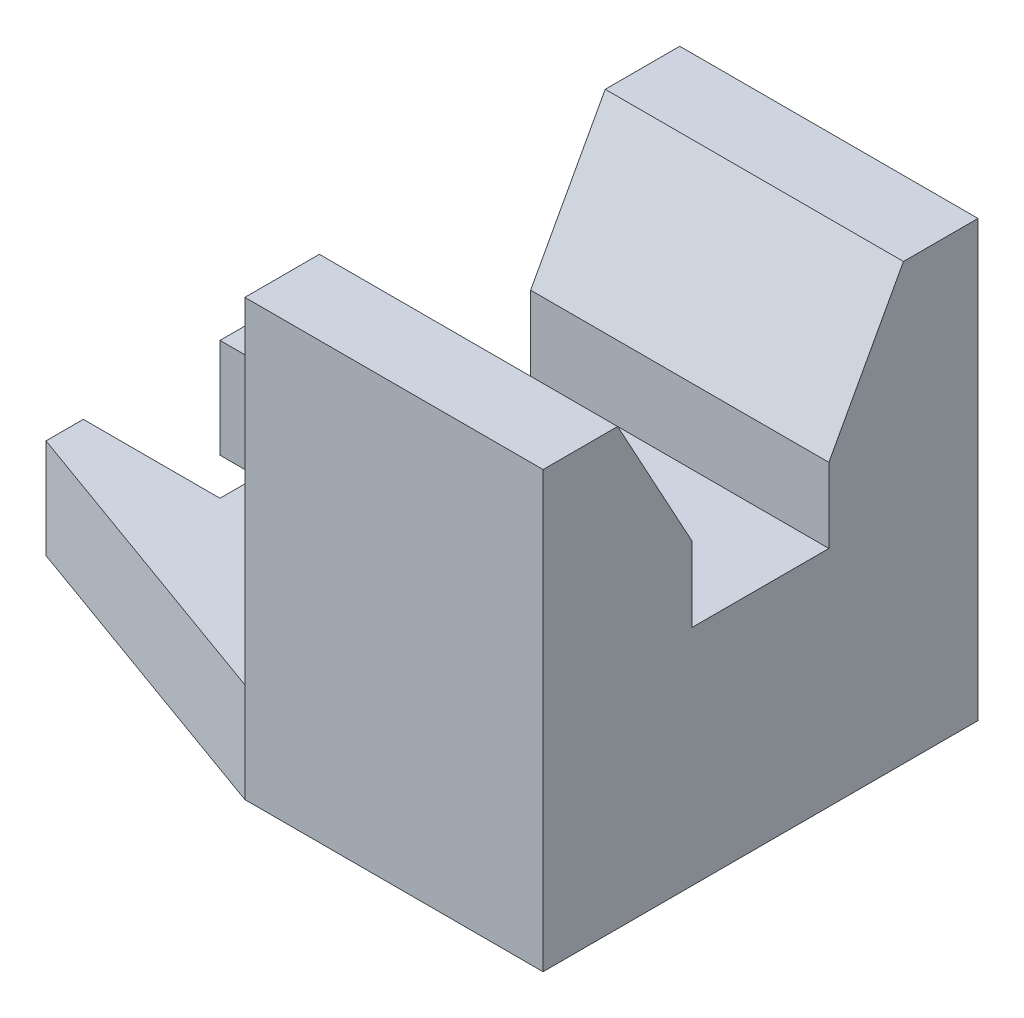
SolidWorks part; units mm, degrees
ref_plane "前视基准面" through (0, 0, 0) normal (0, 0, 1) x (1, 0, 0)
ref_plane "上视基准面" through (0, 0, 0) normal (0, 1, 0) x (1, 0, 0)
ref_plane "右视基准面" through (0, 0, 0) normal (1, 0, 0) x (0, 0, -1)
other "Configuration Table"
sketch "草图4" plane through (0, 0, 0) normal (0, 1, 0) x (1, 0, 0)
  line L0 (-12, 17.5) -> (-37, 8.5)
  line L1 (-12, -17.5) -> (12, -17.5)
  line L3 (-12, 17.5) -> (12, 17.5)
  line L4 (12, -17.5) -> (12, 17.5)
  line L5 (-12, -17.5) -> (12, 17.5) construction
  line L6 (-12, 17.5) -> (12, -17.5) construction
  line L7 (-37, 8.5) -> (-37, 5.5)
  line L8 (-37, 5.5) -> (-26, 5.5)
  line L9 (-26, 5.5) -> (-26, -5.5)
  line L10 (-1119.762, 0) -> (54868.3369, 0) construction
  line L11 (-12, -17.5) -> (-37, -8.5)
  line L12 (-37, -5.5) -> (-26, -5.5)
  line L13 (-37, -8.5) -> (-37, -5.5)
  point P0 (0, 0)
  point P14 (-26, 0)
  dimension "D1" = 17
  dimension "D2" = 11
  dimension "D3" = 11
  dimension "D4" = 24
  dimension "D5" = 49
  dimension "D6" = 35
extrude "凸台-拉伸2" add sketch "草图4" along normal blind 8
sketch "草图5" plane through (0, 8, 0) normal (0, 1, 0) x (1, 0, 0)
  line L1 (12, 17.5) -> (-12, 17.5)
  line L2 (12, 17.5) -> (12, -17.5)
  line L3 (12, -17.5) -> (-12, -17.5)
  line L4 (-12, 17.5) -> (-12, -17.5)
extrude "凸台-拉伸3" add sketch "草图5" along normal blind 27
sketch "草图6" plane through (-12, 0, 0) normal (-1, 0, 0) x (0, 0, 1)
  line L0 (0, -965) -> (0, 49035) construction
  line L1 (-17.5, 35) -> (17.5, 35) construction
  line L2 (-11.5, 35) -> (-5.5, 24)
  line L3 (-5.5, 24) -> (-5.5, 18)
  line L4 (-5.5, 18) -> (5.5, 18)
  line L5 (-11.5, 35) -> (11.5, 35)
  line L6 (5.5, 24) -> (5.5, 18)
  line L7 (11.5, 35) -> (5.5, 24)
  point P5 (0, 35)
  point P11 (0, 35)
  point P12 (0, 18)
  dimension "D1" = 23
  dimension "D2" = 11
  dimension "D3" = 11
  dimension "D4" = 17
extrude "切除-拉伸1" cut sketch "草图6" against normal blind 27
